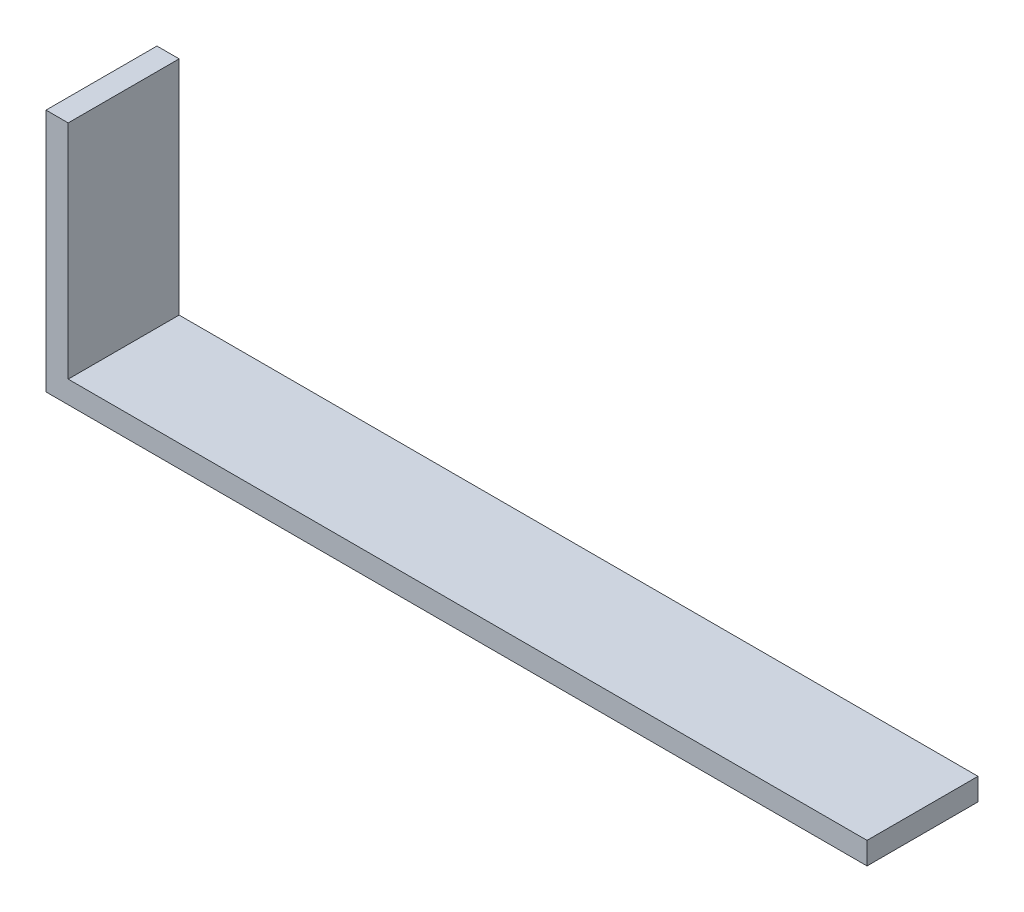
SolidWorks part; units mm, degrees
ref_plane "Front Plane" through (0, 0, 0) normal (0, 0, 1) x (1, 0, 0)
ref_plane "Top Plane" through (0, 0, 0) normal (0, 1, 0) x (1, 0, 0)
ref_plane "Right Plane" through (0, 0, 0) normal (1, 0, 0) x (0, 0, -1)
sketch "Sketch1" plane through (0, 0, 0) normal (0, 0, 1) x (1, 0, 0)
  line L0 (0, 5.9813) -> (0, -7.9887)
  line L1 (0, -7.9887) -> (46.99, -7.9887)
  line L2 (46.99, -7.9887) -> (46.99, -6.7187)
  line L3 (46.99, -6.7187) -> (1.27, -6.7187)
  line L4 (1.27, -6.7187) -> (1.27, 5.9813)
  line L5 (1.27, 5.9813) -> (0, 5.9813)
  dimension "D1" = 12.7
  dimension "D2" = 45.72
  dimension "D3" = 12.7
  dimension "D4" = 1.27
  dimension "D5" = 1.27
  dimension "D6" = 46.99
extrude "Boss-Extrude1" add sketch "Sketch1" along normal blind 6.35
